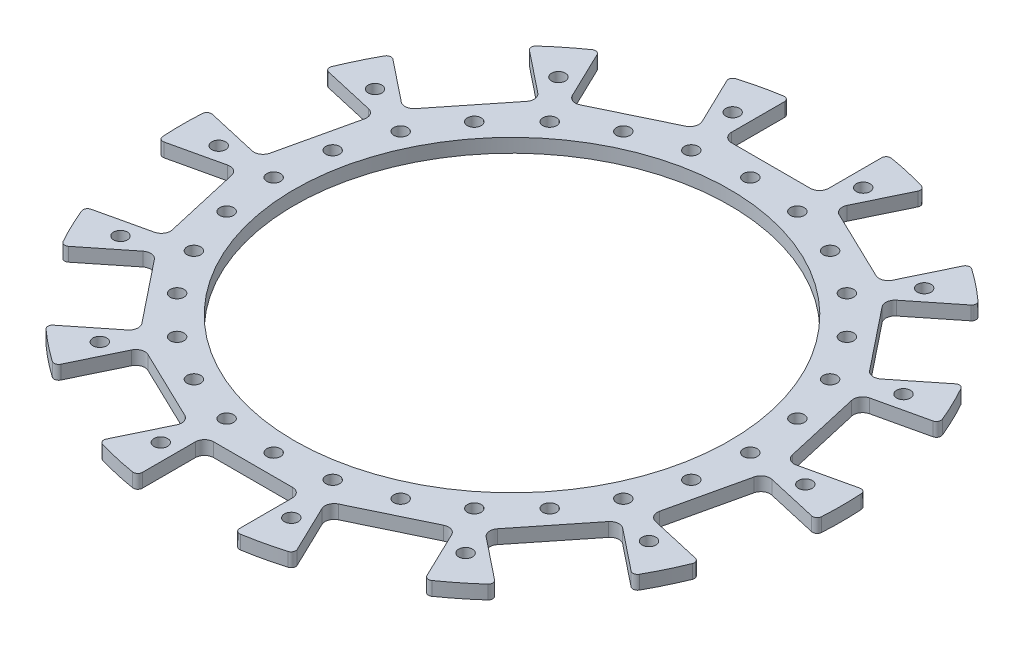
SolidWorks part; units mm, degrees
material "Thornel Mat VMA"
ref_plane "前视基准面" through (0, 0, 0) normal (0, 0, 1) x (1, 0, 0)
ref_plane "上视基准面" through (0, 0, 0) normal (0, 1, 0) x (1, 0, 0)
ref_plane "右视基准面" through (0, 0, 0) normal (1, 0, 0) x (0, 0, -1)
sketch "草图1" plane through (0, 0, 0) normal (0, 1, 0) x (1, 0, 0)
  line L0 (0, 0) -> (0, -67) construction
  line L1 (13, -67) -> (-13, -67) construction
  line L2 (-13, -68.5) -> (-13, -65.5)
  line L3 (0, -67) -> (0, -69.5129) construction
  line L4 (-10.1, -69.5129) -> (10.1, -69.5129) construction
  line L5 (-13, -68.5) -> (-10.6, -68.5)
  line L6 (-10.6, -68.5) -> (-10.6, -71.2154)
  line L7 (-13, -65.5) -> (-10.6, -65.5)
  line L8 (-10.6, -65.5) -> (-10.6, -56.5)
  line L9 (-10.6, -56.5) -> (10.6, -56.5)
  line L10 (10.6, -68.5) -> (10.6, -71.2154)
  line L11 (13, -68.5) -> (10.6, -68.5)
  line L12 (13, -68.5) -> (13, -65.5)
  line L13 (13, -65.5) -> (10.6, -65.5)
  line L14 (10.6, -65.5) -> (10.6, -56.5)
  line L15 (-34.0647, -46.3056) -> (-14.9642, -55.5039)
  line L16 (-37.9697, -54.4143) -> (-34.0647, -46.3056)
  line L17 (-40.132, -53.373) -> (-37.9697, -54.4143)
  line L18 (-41.4336, -56.0759) -> (-40.132, -53.373)
  line L19 (-41.4336, -56.0759) -> (-39.2713, -57.1172)
  line L20 (-39.2713, -57.1172) -> (-40.4495, -59.5637)
  line L21 (-20.1708, -66.3155) -> (-21.349, -68.7621)
  line L22 (-18.0084, -67.3569) -> (-20.1708, -66.3155)
  line L23 (-18.0084, -67.3569) -> (-16.7068, -64.6539)
  line L24 (-16.7068, -64.6539) -> (-18.8691, -63.6126)
  line L25 (-18.8691, -63.6126) -> (-14.9642, -55.5039)
  line L26 (-50.7825, -26.9398) -> (-37.5645, -43.5146)
  line L27 (-57.819, -32.5512) -> (-50.7825, -26.9398)
  line L28 (-59.3153, -30.6748) -> (-57.819, -32.5512)
  line L29 (-61.6608, -32.5452) -> (-59.3153, -30.6748)
  line L30 (-61.6608, -32.5452) -> (-60.1644, -34.4216)
  line L31 (-60.1644, -34.4216) -> (-62.2875, -36.1147)
  line L32 (-46.9465, -50.9965) -> (-49.0695, -52.6895)
  line L33 (-45.4501, -52.8729) -> (-46.9465, -50.9965)
  line L34 (-45.4501, -52.8729) -> (-43.1046, -51.0024)
  line L35 (-43.1046, -51.0024) -> (-44.601, -49.126)
  line L36 (-44.601, -49.126) -> (-37.5645, -43.5146)
  line L37 (-57.4421, -2.2382) -> (-52.7247, -22.9067)
  line L38 (-66.2165, -4.2409) -> (-57.4421, -2.2382)
  line L39 (-66.7506, -1.9011) -> (-66.2165, -4.2409)
  line L40 (-69.6753, -2.5686) -> (-66.7506, -1.9011)
  line L41 (-69.6753, -2.5686) -> (-69.1413, -4.9084)
  line L42 (-69.1413, -4.9084) -> (-71.7886, -5.5127)
  line L43 (-64.4238, -25.5769) -> (-67.0712, -26.1812)
  line L44 (-63.8898, -27.9167) -> (-64.4238, -25.5769)
  line L45 (-63.8898, -27.9167) -> (-60.965, -27.2492)
  line L46 (-60.965, -27.2492) -> (-61.4991, -24.9094)
  line L47 (-61.4991, -24.9094) -> (-52.7247, -22.9067)
  line L48 (-52.7247, 22.9067) -> (-57.4421, 2.2382)
  line L49 (-61.4991, 24.9094) -> (-52.7247, 22.9067)
  line L50 (-60.965, 27.2492) -> (-61.4991, 24.9094)
  line L51 (-63.8898, 27.9167) -> (-60.965, 27.2492)
  line L52 (-63.8898, 27.9167) -> (-64.4238, 25.5769)
  line L53 (-64.4238, 25.5769) -> (-67.0712, 26.1812)
  line L54 (-69.1413, 4.9084) -> (-71.7886, 5.5127)
  line L55 (-69.6753, 2.5686) -> (-69.1413, 4.9084)
  line L56 (-69.6753, 2.5686) -> (-66.7506, 1.9011)
  line L57 (-66.7506, 1.9011) -> (-66.2165, 4.2409)
  line L58 (-66.2165, 4.2409) -> (-57.4421, 2.2382)
  line L59 (-37.5645, 43.5146) -> (-50.7825, 26.9398)
  line L60 (-44.601, 49.126) -> (-37.5645, 43.5146)
  line L61 (-43.1046, 51.0024) -> (-44.601, 49.126)
  line L62 (-45.4501, 52.8729) -> (-43.1046, 51.0024)
  line L63 (-45.4501, 52.8729) -> (-46.9465, 50.9965)
  line L64 (-46.9465, 50.9965) -> (-49.0695, 52.6895)
  line L65 (-60.1644, 34.4216) -> (-62.2875, 36.1147)
  line L66 (-61.6608, 32.5452) -> (-60.1644, 34.4216)
  line L67 (-61.6608, 32.5452) -> (-59.3153, 30.6748)
  line L68 (-59.3153, 30.6748) -> (-57.819, 32.5512)
  line L69 (-57.819, 32.5512) -> (-50.7825, 26.9398)
  line L70 (-14.9642, 55.5039) -> (-34.0647, 46.3056)
  line L71 (-18.8691, 63.6126) -> (-14.9642, 55.5039)
  line L72 (-16.7068, 64.6539) -> (-18.8691, 63.6126)
  line L73 (-18.0084, 67.3569) -> (-16.7068, 64.6539)
  line L74 (-18.0084, 67.3569) -> (-20.1708, 66.3155)
  line L75 (-20.1708, 66.3155) -> (-21.349, 68.7621)
  line L76 (-39.2713, 57.1172) -> (-40.4495, 59.5637)
  line L77 (-41.4336, 56.0759) -> (-39.2713, 57.1172)
  line L78 (-41.4336, 56.0759) -> (-40.132, 53.373)
  line L79 (-40.132, 53.373) -> (-37.9697, 54.4143)
  line L80 (-37.9697, 54.4143) -> (-34.0647, 46.3056)
  line L81 (10.6, 56.5) -> (-10.6, 56.5)
  line L82 (10.6, 65.5) -> (10.6, 56.5)
  line L83 (13, 65.5) -> (10.6, 65.5)
  line L84 (13, 68.5) -> (13, 65.5)
  line L85 (13, 68.5) -> (10.6, 68.5)
  line L86 (10.6, 68.5) -> (10.6, 71.2154)
  line L87 (-10.6, 68.5) -> (-10.6, 71.2154)
  line L88 (-13, 68.5) -> (-10.6, 68.5)
  line L89 (-13, 68.5) -> (-13, 65.5)
  line L90 (-13, 65.5) -> (-10.6, 65.5)
  line L91 (-10.6, 65.5) -> (-10.6, 56.5)
  line L92 (34.0647, 46.3056) -> (14.9642, 55.5039)
  line L93 (37.9697, 54.4143) -> (34.0647, 46.3056)
  line L94 (40.132, 53.373) -> (37.9697, 54.4143)
  line L95 (41.4336, 56.0759) -> (40.132, 53.373)
  line L96 (41.4336, 56.0759) -> (39.2713, 57.1172)
  line L97 (39.2713, 57.1172) -> (40.4495, 59.5637)
  line L98 (20.1708, 66.3155) -> (21.349, 68.7621)
  line L99 (18.0084, 67.3569) -> (20.1708, 66.3155)
  line L100 (18.0084, 67.3569) -> (16.7068, 64.6539)
  line L101 (16.7068, 64.6539) -> (18.8691, 63.6126)
  line L102 (18.8691, 63.6126) -> (14.9642, 55.5039)
  line L103 (50.7825, 26.9398) -> (37.5645, 43.5146)
  line L104 (57.819, 32.5512) -> (50.7825, 26.9398)
  line L105 (59.3153, 30.6748) -> (57.819, 32.5512)
  line L106 (61.6608, 32.5452) -> (59.3153, 30.6748)
  line L107 (61.6608, 32.5452) -> (60.1644, 34.4216)
  line L108 (60.1644, 34.4216) -> (62.2875, 36.1147)
  line L109 (46.9465, 50.9965) -> (49.0695, 52.6895)
  line L110 (45.4501, 52.8729) -> (46.9465, 50.9965)
  line L111 (45.4501, 52.8729) -> (43.1046, 51.0024)
  line L112 (43.1046, 51.0024) -> (44.601, 49.126)
  line L113 (44.601, 49.126) -> (37.5645, 43.5146)
  line L114 (57.4421, 2.2382) -> (52.7247, 22.9067)
  line L115 (66.2165, 4.2409) -> (57.4421, 2.2382)
  line L116 (66.7506, 1.9011) -> (66.2165, 4.2409)
  line L117 (69.6753, 2.5686) -> (66.7506, 1.9011)
  line L118 (69.6753, 2.5686) -> (69.1413, 4.9084)
  line L119 (69.1413, 4.9084) -> (71.7886, 5.5127)
  line L120 (64.4238, 25.5769) -> (67.0712, 26.1812)
  line L121 (63.8898, 27.9167) -> (64.4238, 25.5769)
  line L122 (63.8898, 27.9167) -> (60.965, 27.2492)
  line L123 (60.965, 27.2492) -> (61.4991, 24.9094)
  line L124 (61.4991, 24.9094) -> (52.7247, 22.9067)
  line L125 (52.7247, -22.9067) -> (57.4421, -2.2382)
  line L126 (61.4991, -24.9094) -> (52.7247, -22.9067)
  line L127 (60.965, -27.2492) -> (61.4991, -24.9094)
  line L128 (63.8898, -27.9167) -> (60.965, -27.2492)
  line L129 (63.8898, -27.9167) -> (64.4238, -25.5769)
  line L130 (64.4238, -25.5769) -> (67.0712, -26.1812)
  line L131 (69.1413, -4.9084) -> (71.7886, -5.5127)
  line L132 (69.6753, -2.5686) -> (69.1413, -4.9084)
  line L133 (69.6753, -2.5686) -> (66.7506, -1.9011)
  line L134 (66.7506, -1.9011) -> (66.2165, -4.2409)
  line L135 (66.2165, -4.2409) -> (57.4421, -2.2382)
  line L136 (37.5645, -43.5146) -> (50.7825, -26.9398)
  line L137 (44.601, -49.126) -> (37.5645, -43.5146)
  line L138 (43.1046, -51.0024) -> (44.601, -49.126)
  line L139 (45.4501, -52.8729) -> (43.1046, -51.0024)
  line L140 (45.4501, -52.8729) -> (46.9465, -50.9965)
  line L141 (46.9465, -50.9965) -> (49.0695, -52.6895)
  line L142 (60.1644, -34.4216) -> (62.2875, -36.1147)
  line L143 (61.6608, -32.5452) -> (60.1644, -34.4216)
  line L144 (61.6608, -32.5452) -> (59.3153, -30.6748)
  line L145 (59.3153, -30.6748) -> (57.819, -32.5512)
  line L146 (57.819, -32.5512) -> (50.7825, -26.9398)
  line L147 (14.9642, -55.5039) -> (34.0647, -46.3056)
  line L148 (18.8691, -63.6126) -> (14.9642, -55.5039)
  line L149 (16.7068, -64.6539) -> (18.8691, -63.6126)
  line L150 (18.0084, -67.3569) -> (16.7068, -64.6539)
  line L151 (18.0084, -67.3569) -> (20.1708, -66.3155)
  line L152 (20.1708, -66.3155) -> (21.349, -68.7621)
  line L153 (39.2713, -57.1172) -> (40.4495, -59.5637)
  line L154 (41.4336, -56.0759) -> (39.2713, -57.1172)
  line L155 (41.4336, -56.0759) -> (40.132, -53.373)
  line L156 (40.132, -53.373) -> (37.9697, -54.4143)
  line L157 (37.9697, -54.4143) -> (34.0647, -46.3056)
  line L158 (-10.6, -65.5) -> (-10.6, -68.5)
  line L159 (10.6, -65.5) -> (10.6, -68.5)
  line L160 (-18.8691, -63.6126) -> (-20.1708, -66.3155)
  line L161 (-37.9697, -54.4143) -> (-39.2713, -57.1172)
  line L162 (-44.601, -49.126) -> (-46.9465, -50.9965)
  line L163 (-57.819, -32.5512) -> (-60.1644, -34.4216)
  line L164 (-61.4991, -24.9094) -> (-64.4238, -25.5769)
  line L165 (-66.2165, -4.2409) -> (-69.1413, -4.9084)
  line L166 (-66.2165, 4.2409) -> (-69.1413, 4.9084)
  line L167 (-61.4991, 24.9094) -> (-64.4238, 25.5769)
  line L168 (-57.819, 32.5512) -> (-60.1644, 34.4216)
  line L169 (-44.601, 49.126) -> (-46.9465, 50.9965)
  line L170 (-37.9697, 54.4143) -> (-39.2713, 57.1172)
  line L171 (-18.8691, 63.6126) -> (-20.1708, 66.3155)
  line L172 (-10.6, 65.5) -> (-10.6, 68.5)
  line L173 (10.6, 65.5) -> (10.6, 68.5)
  line L174 (18.8691, 63.6126) -> (20.1708, 66.3155)
  line L175 (37.9697, 54.4143) -> (39.2713, 57.1172)
  line L176 (44.601, 49.126) -> (46.9465, 50.9965)
  line L177 (57.819, 32.5512) -> (60.1644, 34.4216)
  line L178 (61.4991, 24.9094) -> (64.4238, 25.5769)
  line L179 (66.2165, 4.2409) -> (69.1413, 4.9084)
  line L180 (66.2165, -4.2409) -> (69.1413, -4.9084)
  line L181 (61.4991, -24.9094) -> (64.4238, -25.5769)
  line L182 (57.819, -32.5512) -> (60.1644, -34.4216)
  line L183 (44.601, -49.126) -> (46.9465, -50.9965)
  line L184 (37.9697, -54.4143) -> (39.2713, -57.1172)
  line L185 (18.8691, -63.6126) -> (20.1708, -66.3155)
  circle A0 centre (0, 0) radius 67 construction
  circle A1 centre (0, 0) radius 72
  point P7 (0, -67)
  point P10 (-13, -67)
  point P21 (0, -69.5129)
  point P26 (0, -56.5)
  point P185 (0, 0)
  point P237 (0, 0)
  dimension "D1" = 134
  dimension "D5" = 144
  dimension "D2" = 26
  dimension "D3" = 3
  dimension "D4" = 20.2
  dimension "D6" = 0.5
  dimension "D7" = 10.5
  dimension "D8" = 14
  dimension "D9" = 14
extrude "凸台-拉伸1" add sketch "草图1" along normal blind 3 contours L10 A1 L152 L151 L150 L149 L148 L147 L157 L156 L155 L154 L153 L141 L140 L139 L138 L137 L136 L146 L145 L144 L143 L142 L130 L129 L128 L127 L126 L125 L135 L134 L133 L132 L131 L119 L118 L117 L116 L115 L114 L124 L123 L122 L121 L120 L108 | L161 L17 L18 L19 | L163 L28 L29 L30 | L35 L162 L33 L34 | L46 L164 L44 L45 | L24 L160 L22 L23 | L158 L7 L2 L5 | L185 L149 L150 L151 | L13 L159 L11 L12 | L156 L184 L154 L155 | L183 L138 L139 L140 | L145 L182 L143 L144 | L181 L127 L128 L129 | L134 L180 L132 L133 | L179 L116 L117 L118 | L177 L105 L106 L107 | L123 L178 L121 L122 | L112 L176 L110 L111 | L175 L94 L95 L96 | L101 L174 L99 L100 | L173 L83 L84 L85 | L171 L72 L73 L74 | L90 L172 L88 L89 | L169 L61 L62 L63 | L79 L170 L77 L78 | L167 L50 L51 L52 | L68 L168 L66 L67 | L165 L39 L40 L41 | L57 L166 L55 L56
fillet "圆角1" radius 2 28 edges at (50.7825, 1.5, 26.9398) (57.4421, 1.5, 2.2382) (52.7247, 1.5, -22.9067) (37.5645, 1.5, -43.5146) (14.9642, 1.5, -55.5039) (-10.6, 1.5, -56.5) (-34.0647, 1.5, -46.3056) (-50.7825, 1.5, -26.9398) (-57.4421, 1.5, -2.2382) (-52.7247, 1.5, 22.9067) (-37.5645, 1.5, 43.5146) (-14.9642, 1.5, 55.5039) (-34.0647, 1.5, 46.3056) (-50.7825, 1.5, 26.9398) (-57.4421, 1.5, 2.2382) (-52.7247, 1.5, -22.9067) (-37.5645, 1.5, -43.5146) (-14.9642, 1.5, -55.5039) (10.6, 1.5, -56.5) (34.0647, 1.5, -46.3056) (57.4421, 1.5, -2.2382) (50.7825, 1.5, -26.9398) (52.7247, 1.5, 22.9067) (37.5645, 1.5, 43.5146) (34.0647, 1.5, 46.3056) (14.9642, 1.5, 55.5039) (10.6, 1.5, 56.5) (-10.6, 1.5, 56.5)
fillet "圆角2" radius 1 28 edges at (-21.349, 1.5, -68.7621) (40.4495, 1.5, 59.5637) (10.6, 1.5, 71.2154) (10.6, 1.5, -71.2154) (-49.0695, 1.5, -52.6895) (62.2875, 1.5, 36.1147) (-67.0712, 1.5, -26.1812) (71.7886, 1.5, 5.5127) (-71.7886, 1.5, 5.5127) (67.0712, 1.5, -26.1812) (-62.2875, 1.5, 36.1147) (49.0695, 1.5, -52.6895) (-40.4495, 1.5, 59.5637) (21.349, 1.5, -68.7621) (-10.6, 1.5, 71.2154) (-10.6, 1.5, -71.2154) (-40.4495, 1.5, -59.5637) (21.349, 1.5, 68.7621) (-62.2875, 1.5, -36.1147) (49.0695, 1.5, 52.6895) (-71.7886, 1.5, -5.5127) (67.0712, 1.5, 26.1812) (-67.0712, 1.5, 26.1812) (71.7886, 1.5, -5.5127) (-21.349, 1.5, 68.7621) (40.4495, 1.5, -59.5637) (-49.0695, 1.5, 52.6895) (62.2875, 1.5, -36.1147)
sketch "草图2" plane through (0, 0, 0) normal (0, 1, 0) x (1, 0, 0)
  line L0 (64, 0) -> (0, 0) construction
  circle A0 centre (64, 0) radius 1.5
  circle A1 centre (57.662, -27.7686) radius 1.5
  circle A2 centre (39.9033, -50.0372) radius 1.5
  circle A3 centre (14.2413, -62.3954) radius 1.5
  circle A4 centre (-14.2413, -62.3954) radius 1.5
  circle A5 centre (-39.9033, -50.0372) radius 1.5
  circle A6 centre (-57.662, -27.7686) radius 1.5
  circle A7 centre (-64, 0) radius 1.5
  circle A8 centre (-57.662, 27.7686) radius 1.5
  circle A9 centre (-39.9033, 50.0372) radius 1.5
  circle A10 centre (-14.2413, 62.3954) radius 1.5
  circle A11 centre (14.2413, 62.3954) radius 1.5
  circle A12 centre (39.9033, 50.0372) radius 1.5
  circle A13 centre (57.662, 27.7686) radius 1.5
  point P32 (0, 0)
  dimension "D1" = 3
  dimension "D2" = 64
  dimension "D3" = 14
extrude "切除-拉伸1" cut sketch "草图2" along normal blind 11
sketch "草图3" plane through (0, 0, 0) normal (0, 1, 0) x (1, 0, 0)
  line L0 (0, -56.5) -> (0, -52.5) construction
  line L1 (-8.6, -56.5) -> (8.6, -56.5) construction
  circle A0 centre (0, 0) radius 9
  circle A1 centre (0, 0) radius 28
  circle A2 centre (0, 0) radius 52.5
  dimension "D1" = 18
  dimension "D2" = 56
  dimension "D3" = 4
extrude "切除-拉伸2" cut sketch "草图3" along normal blind 11 contours A0 | A2 A1 | A1 A0
sketch "草图9" plane through (0, 3, 0) normal (0, 1, 0) x (1, 0, 0)
  circle A0 centre (0, 0) radius 52.5
  circle A1 centre (0, 0) radius 47.5
  dimension "D1" = 105
  dimension "D2" = 95
extrude "凸台-拉伸2" add sketch "草图9" against normal blind 3
sketch "草图10" plane through (0, 3, 0) normal (0, 1, 0) x (1, 0, 0)
  circle A0 centre (0, 0) radius 52 construction
  circle A1 centre (0, 52) radius 1.5
  circle A2 centre (11.5711, 50.6963) radius 1.5
  circle A3 centre (22.562, 46.8504) radius 1.5
  circle A4 centre (32.4215, 40.6552) radius 1.5
  circle A5 centre (40.6552, 32.4215) radius 1.5
  circle A6 centre (46.8504, 22.562) radius 1.5
  circle A7 centre (50.6963, 11.5711) radius 1.5
  circle A8 centre (52, 0) radius 1.5
  circle A9 centre (50.6963, -11.5711) radius 1.5
  circle A10 centre (46.8504, -22.562) radius 1.5
  circle A11 centre (40.6552, -32.4215) radius 1.5
  circle A12 centre (32.4215, -40.6552) radius 1.5
  circle A13 centre (22.562, -46.8504) radius 1.5
  circle A14 centre (11.5711, -50.6963) radius 1.5
  circle A15 centre (0, -52) radius 1.5
  circle A16 centre (-11.5711, -50.6963) radius 1.5
  circle A17 centre (-22.562, -46.8504) radius 1.5
  circle A18 centre (-32.4215, -40.6552) radius 1.5
  circle A19 centre (-40.6552, -32.4215) radius 1.5
  circle A20 centre (-46.8504, -22.562) radius 1.5
  circle A21 centre (-50.6963, -11.5711) radius 1.5
  circle A22 centre (-52, 0) radius 1.5
  circle A23 centre (-50.6963, 11.5711) radius 1.5
  circle A24 centre (-46.8504, 22.562) radius 1.5
  circle A25 centre (-40.6552, 32.4215) radius 1.5
  circle A26 centre (-32.4215, 40.6552) radius 1.5
  circle A27 centre (-22.562, 46.8504) radius 1.5
  circle A28 centre (-11.5711, 50.6963) radius 1.5
  point P5 (-47.8014, 35.2272)
  point P6 (0, 0)
  point P62 (0, 0)
  dimension "D1" = 104
  dimension "D2" = 3
  dimension "D3" = 28
extrude "切除-拉伸3" cut sketch "草图10" against normal blind 3
